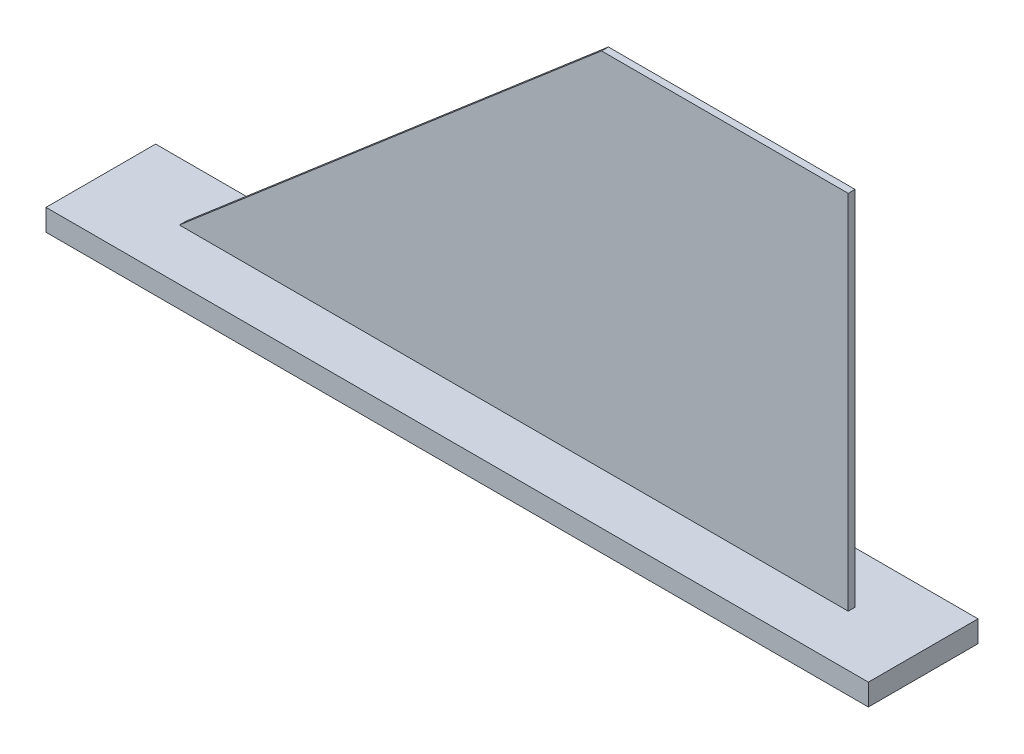
SolidWorks part; units mm, degrees
ref_plane "Front Plane" through (0, 0, 0) normal (0, 0, 1) x (1, 0, 0)
ref_plane "Top Plane" through (0, 0, 0) normal (0, 1, 0) x (1, 0, 0)
ref_plane "Right Plane" through (0, 0, 0) normal (1, 0, 0) x (0, 0, -1)
sketch "Sketch1" plane through (0, 0, 0) normal (0, 1, 0) x (1, 0, 0)
  line L1 (0, 0) -> (381, 0)
  line L2 (0, 0) -> (0, 50.8)
  line L3 (0, 50.8) -> (381, 50.8)
  line L4 (381, 0) -> (381, 50.8)
  dimension "D1" = 381
  dimension "D2" = 50.8
extrude "Boss-Extrude1" add sketch "Sketch1" along normal blind 10
ref_plane "Plane1" through (0, 0, -25.4) normal (0, 0, 1) x (1, 0, 0)
sketch "Sketch2" plane through (0, 0, -25.4) normal (0, 0, 1) x (1, 0, 0)
  line L0 (347.868, 10) -> (37.988, 10)
  line L1 (0, 10) -> (381, 10) construction
  line L2 (37.988, 10) -> (233.568, 177.64)
  line L3 (233.568, 177.64) -> (347.868, 177.64)
  line L4 (347.868, 177.64) -> (347.868, 10)
  point P6 (37.988, 10)
  dimension "D1" = 309.88
  dimension "D2" = 167.64
  dimension "D3" = 114.3
extrude "Boss-Extrude2" add sketch "Sketch2" along normal blind 1.5875 and the other way blind 1.5875 separate body
